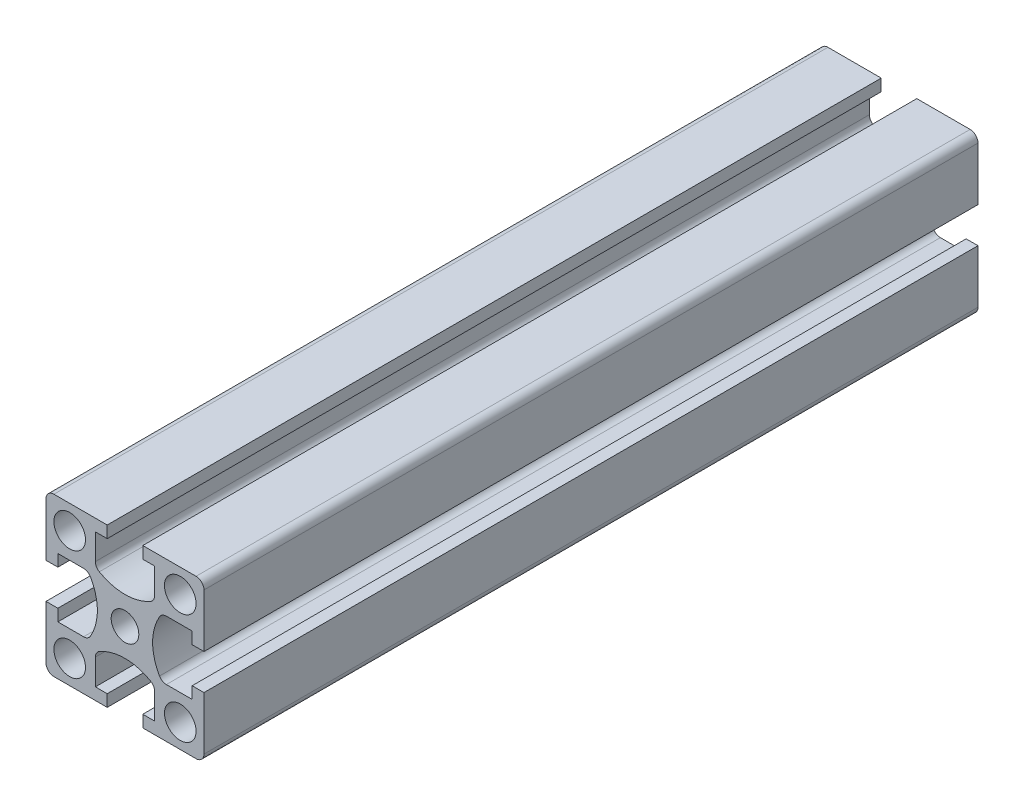
SolidWorks part; units mm, degrees
ref_plane "Front Plane" through (0, 0, 0) normal (0, 0, 1) x (1, 0, 0)
ref_plane "Top Plane" through (0, 0, 0) normal (0, 1, 0) x (1, 0, 0)
ref_plane "Right Plane" through (0, 0, 0) normal (1, 0, 0) x (0, 0, -1)
sketch "Sketch1" plane through (0, 0, 0) normal (0, 0, 1) x (1, 0, 0)
  line L64 (-10, 9) -> (-10, 2.25)
  line L65 (-10, 2.25) -> (-8.5, 2.25)
  line L66 (-8.5, 2.25) -> (-8.5, 3.75)
  line L67 (-8.5, 3.75) -> (-5.2369, 3.75)
  line L68 (-5.2369, -3.75) -> (-8.5, -3.75)
  line L69 (-8.5, -3.75) -> (-8.5, -2.25)
  line L70 (-8.5, -2.25) -> (-10, -2.25)
  line L71 (-10, -2.25) -> (-10, -9)
  line L72 (-9, -10) -> (-2.25, -10)
  line L73 (-2.25, -10) -> (-2.25, -8.5)
  line L74 (-2.25, -8.5) -> (-3.75, -8.5)
  line L75 (-3.75, -8.5) -> (-3.75, -5.2369)
  line L76 (3.75, -5.2369) -> (3.75, -8.5)
  line L77 (3.75, -8.5) -> (2.25, -8.5)
  line L78 (2.25, -8.5) -> (2.25, -10)
  line L79 (2.25, -10) -> (9, -10)
  line L80 (10, -9) -> (10, -2.25)
  line L81 (10, -2.25) -> (8.5, -2.25)
  line L82 (8.5, -2.25) -> (8.5, -3.75)
  line L83 (8.5, -3.75) -> (5.2369, -3.75)
  line L84 (5.2369, 3.75) -> (8.5, 3.75)
  line L85 (8.5, 3.75) -> (8.5, 2.25)
  line L86 (8.5, 2.25) -> (10, 2.25)
  line L87 (10, 2.25) -> (10, 9)
  line L88 (9, 10) -> (2.25, 10)
  line L89 (2.25, 10) -> (2.25, 8.5)
  line L90 (2.25, 8.5) -> (3.75, 8.5)
  line L91 (3.75, 8.5) -> (3.75, 5.2369)
  line L92 (-3.75, 5.2369) -> (-3.75, 8.5)
  line L93 (-3.75, 8.5) -> (-2.25, 8.5)
  line L94 (-2.25, 8.5) -> (-2.25, 10)
  line L95 (-2.25, 10) -> (-9, 10)
  circle A5 centre (-7, -7) radius 2
  circle A6 centre (7, -7) radius 2
  circle A7 centre (7, 7) radius 2
  circle A8 centre (0, 0) radius 1.75
  circle A9 centre (-7, 7) radius 2
  arc A32 (-9, 10) -> (-10, 9) centre (-9, 9) ccw
  arc A33 (-4.3708, 3.25) -> (-5.2369, 3.75) centre (-5.2369, 2.75) ccw
  arc A34 (-4.3708, -3.25) -> (-4.3708, 3.25) centre (-10, 0) ccw
  arc A35 (-5.2369, -3.75) -> (-4.3708, -3.25) centre (-5.2369, -2.75) ccw
  arc A36 (-10, -9) -> (-9, -10) centre (-9, -9) ccw
  arc A37 (-3.25, -4.3708) -> (-3.75, -5.2369) centre (-2.75, -5.2369) ccw
  arc A38 (3.25, -4.3708) -> (-3.25, -4.3708) centre (0, -10) ccw
  arc A39 (3.75, -5.2369) -> (3.25, -4.3708) centre (2.75, -5.2369) ccw
  arc A40 (9, -10) -> (10, -9) centre (9, -9) ccw
  arc A41 (4.3708, -3.25) -> (5.2369, -3.75) centre (5.2369, -2.75) ccw
  arc A42 (4.3708, 3.25) -> (4.3708, -3.25) centre (10, 0) ccw
  arc A43 (5.2369, 3.75) -> (4.3708, 3.25) centre (5.2369, 2.75) ccw
  arc A44 (10, 9) -> (9, 10) centre (9, 9) ccw
  arc A45 (3.25, 4.3708) -> (3.75, 5.2369) centre (2.75, 5.2369) ccw
  arc A46 (-3.25, 4.3708) -> (3.25, 4.3708) centre (0, 10) ccw
  arc A47 (-3.75, 5.2369) -> (-3.25, 4.3708) centre (-2.75, 5.2369) ccw
extrude "Boss-Extrude1" add sketch "Sketch1" along normal blind 98
